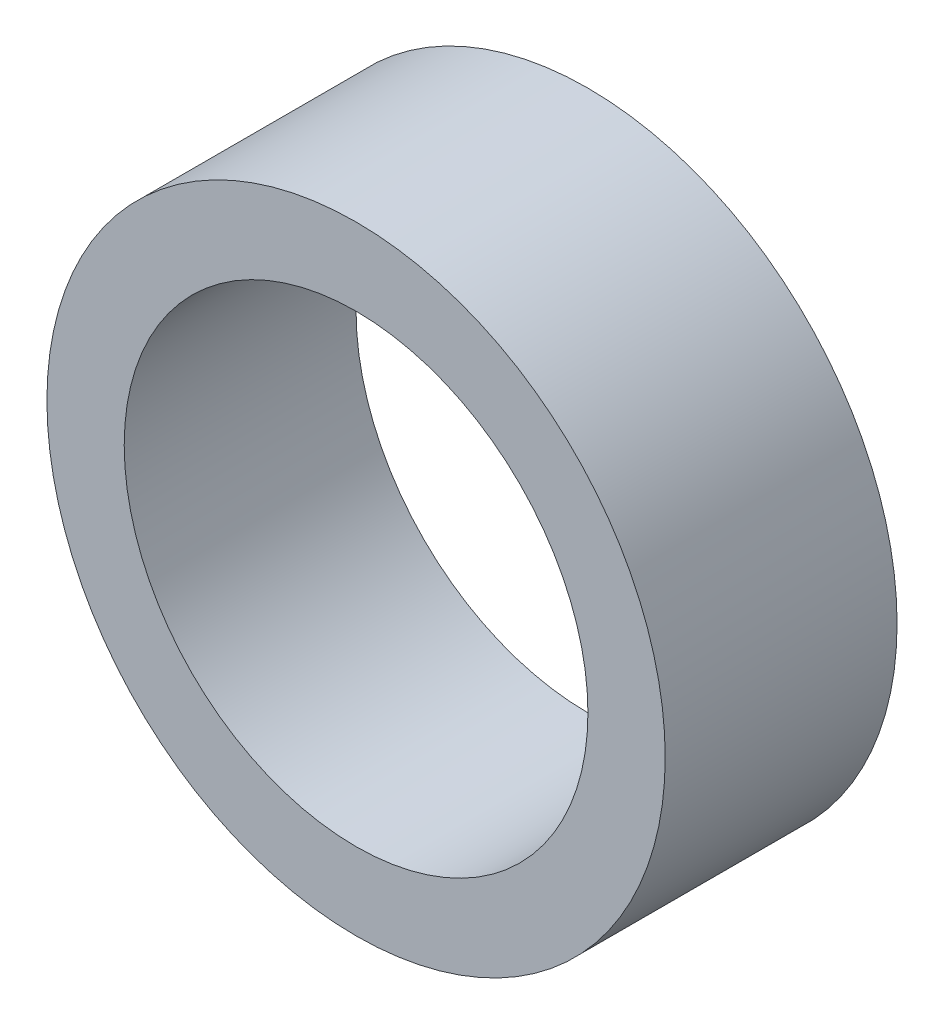
SolidWorks part; units mm, degrees
ref_plane "前视基准面" through (0, 0, 0) normal (0, 0, 1) x (1, 0, 0)
ref_plane "上视基准面" through (0, 0, 0) normal (0, 1, 0) x (1, 0, 0)
ref_plane "右视基准面" through (0, 0, 0) normal (1, 0, 0) x (0, 0, -1)
other "Configuration Table"
sketch "草图1" plane through (0, 0, 0) normal (0, 0, 1) x (1, 0, 0)
  circle A0 centre (0, 0) radius 3
  circle A1 centre (0, 0) radius 4
  dimension "D1" = 8
  dimension "D2" = 6
extrude "凸台-拉伸1" add sketch "草图1" along normal blind 3
